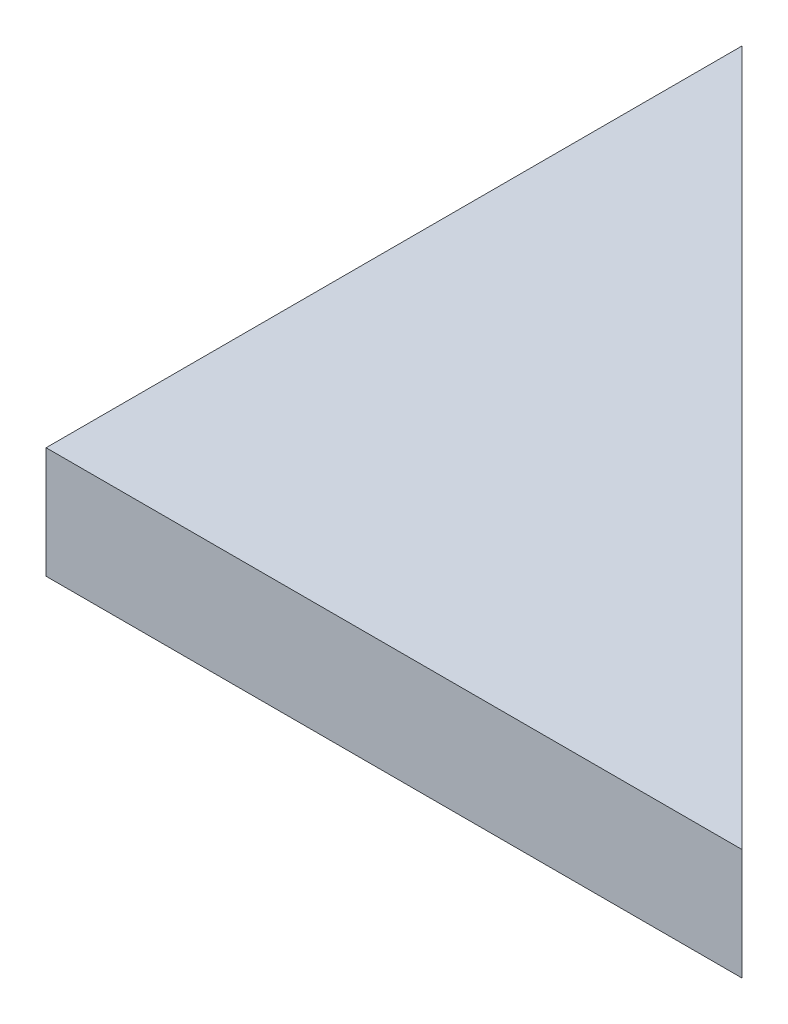
SolidWorks part; units mm, degrees
ref_plane "Спереди" through (0, 0, 0) normal (0, 0, 1) x (1, 0, 0)
ref_plane "Сверху" through (0, 0, 0) normal (0, 1, 0) x (1, 0, 0)
ref_plane "Справа" through (0, 0, 0) normal (1, 0, 0) x (0, 0, -1)
sketch "Эскиз1" plane through (0, 0, 0) normal (0, 1, 0) x (1, 0, 0)
  line L0 (0, 0) -> (0, 25)
  line L1 (0, 0) -> (25, 0)
  line L2 (0, 25) -> (25, 0)
extrude "Вытянуть1" add sketch "Эскиз1" along normal blind 4
